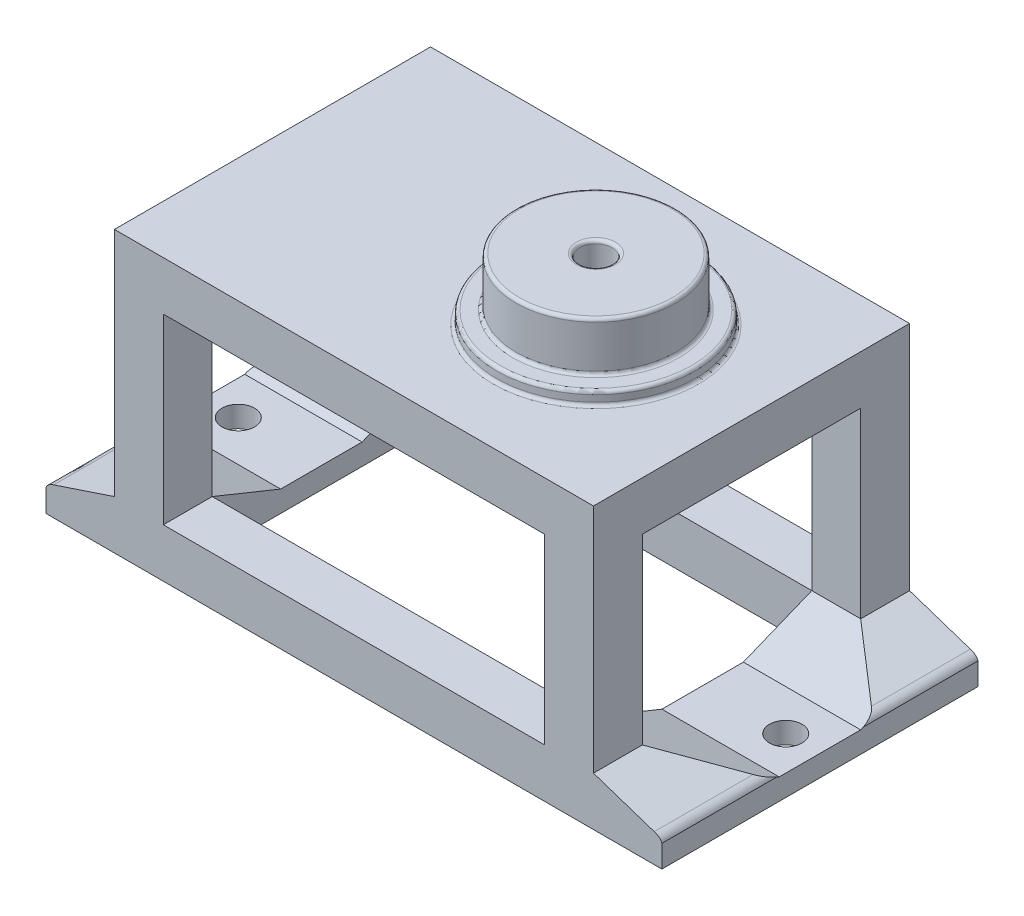
SolidWorks part; units mm, degrees
ref_plane "前视基准面" through (0, 0, 0) normal (0, 0, 1) x (1, 0, 0)
ref_plane "上视基准面" through (0, 0, 0) normal (0, 1, 0) x (1, 0, 0)
ref_plane "右视基准面" through (0, 0, 0) normal (1, 0, 0) x (0, 0, -1)
sketch "草图1" plane through (0, 0, 0) normal (0, 1, 0) x (1, 0, 0)
  line L1 (-11.7, 6.7) -> (11.7, 6.7)
  line L2 (-11.7, 6.7) -> (-11.7, -6.7)
  line L3 (-11.7, -6.7) -> (11.7, -6.7)
  line L4 (11.7, 6.7) -> (11.7, -6.7)
  line L5 (-11.7, 6.7) -> (11.7, -6.7) construction
  line L6 (-11.7, -6.7) -> (11.7, 6.7) construction
  line L7 (-14.7, 9.7) -> (14.7, 9.7)
  line L8 (-14.7, 9.7) -> (-14.7, -9.7)
  line L9 (-14.7, -9.7) -> (14.7, -9.7)
  line L10 (14.7, 9.7) -> (14.7, -9.7)
  line L11 (-14.7, 9.7) -> (14.7, -9.7) construction
  line L12 (-14.7, -9.7) -> (14.7, 9.7) construction
  point P0 (0, 0)
  point P6 (0, 0)
  dimension "D1" = 23.4
  dimension "D2" = 13.4
  dimension "D3" = 3
  dimension "D4" = 3
extrude "凸台-拉伸1" add sketch "草图1" along normal blind 16.4
sketch "草图2" plane through (0, 16.4, 0) normal (0, 1, 0) x (1, 0, 0)
  line L1 (-14.7, -9.7) -> (14.7, -9.7)
  line L2 (-14.7, -9.7) -> (-14.7, 9.7)
  line L3 (-14.7, 9.7) -> (14.7, 9.7)
  line L4 (14.7, -9.7) -> (14.7, 9.7)
  line L5 (-14.7, -9.7) -> (14.7, 9.7) construction
  line L6 (-14.7, 9.7) -> (14.7, -9.7) construction
  point P0 (0, 0)
extrude "凸台-拉伸2" add sketch "草图2" along normal blind 0.8
sketch "草图3" plane through (0, 17.2, 0) normal (0, 1, 0) x (1, 0, 0)
  line L0 (11.25, 0) -> (5.15, 0)
  line L1 (-11.25, 6.1) -> (11.25, 6.1)
  line L2 (-11.25, 6.1) -> (-11.25, -6.1)
  line L3 (-11.25, -6.1) -> (11.25, -6.1)
  line L4 (11.25, 6.1) -> (11.25, -6.1)
  line L5 (-11.25, 6.1) -> (11.25, -6.1) construction
  line L6 (-11.25, -6.1) -> (11.25, 6.1) construction
  circle A0 centre (5.15, 0) radius 6.1
  point P0 (0, 0)
  dimension "D1" = 22.5
  dimension "D2" = 12.2
extrude "凸台-拉伸3" add sketch "草图3" along normal blind 0.8
sketch "草图5" plane through (0, 18, 0) normal (0, 1, 0) x (1, 0, 0)
  circle A0 centre (5.15, 0) radius 4.9
  circle A1 centre (5.15, 0) radius 1
extrude "凸台-拉伸4" add sketch "草图5" along normal blind 3
fillet "圆角1" radius 0.2 6 edges at (5.15, 18, 6.1) (5.15, 21, 4.9) (5.15, 18, 4.9) (5.15, 17.2, 6.1) (5.15, 18, 1) (5.15, 21, 1)
sketch "草图6" plane through (0, 21, 0) normal (0, 1, 0) x (1, 0, 0)
sketch "草图7" plane through (-14.7, 0, 0) normal (-1, 0, 0) x (0, 0, 1)
  line L0 (9.7, 8.6) -> (-9.7, 8.6)
  line L1 (9.7, 17.2) -> (9.7, 0) construction
  line L2 (-9.7, 17.2) -> (-9.7, 0) construction
  line L3 (-9.7, 0) -> (9.7, 0) construction
  line L4 (6.7, 14.2) -> (-6.7, 14.2)
  line L5 (6.7, 14.2) -> (6.7, 3)
  line L6 (6.7, 3) -> (-6.7, 3)
  line L7 (-6.7, 14.2) -> (-6.7, 3)
  line L8 (6.7, 14.2) -> (-6.7, 3) construction
  line L9 (6.7, 3) -> (-6.7, 14.2) construction
  point P6 (0, 8.6)
  dimension "D1" = 3
  dimension "D2" = 3
extrude "切除-拉伸2" cut sketch "草图7" against normal blind 30 contours L4 L7 L0 L5 | L0 L7 L6 L5
sketch "草图8" plane through (0, 0, -9.7) normal (0, 0, -1) x (-1, 0, 0)
  line L0 (-14.7, 8.6) -> (14.7, 8.6)
  line L1 (-14.7, 17.2) -> (-14.7, 0) construction
  line L2 (14.7, 17.2) -> (14.7, 0) construction
  line L3 (-14.7, 17.2) -> (14.7, 17.2) construction
  line L4 (-11.7, 14.2) -> (11.7, 14.2)
  line L5 (-11.7, 14.2) -> (-11.7, 3)
  line L6 (-11.7, 3) -> (11.7, 3)
  line L7 (11.7, 14.2) -> (11.7, 3)
  line L8 (-11.7, 14.2) -> (11.7, 3) construction
  line L9 (-11.7, 3) -> (11.7, 14.2) construction
  point P6 (0, 8.6)
  dimension "D1" = 3
  dimension "D2" = 3
extrude "切除-拉伸3" cut sketch "草图8" against normal blind 30 contours L7 L4 L5 L0 | L7 L0 L5 L6
sketch "草图9" plane through (14.7, 0, 0) normal (1, 0, 0) x (0, 0, -1)
  line L1 (9.7, 0) -> (-9.7, 0)
  line L2 (9.7, 0) -> (9.7, 3)
  line L3 (9.7, 3) -> (-9.7, 3)
  line L4 (-9.7, 0) -> (-9.7, 3)
extrude "凸台-拉伸5" add sketch "草图9" along normal blind 4.2
sketch "草图10" plane through (0, 0, 9.7) normal (0, 0, 1) x (1, 0, 0)
  line L0 (18.9, 1.3692) -> (18.9, 1.6)
  line L1 (18.9, 3) -> (18.9, 0) construction
  line L2 (18.9, 3) -> (18.9, 1.6)
  line L3 (18.4866, 1.7378) -> (14.7, 3)
  line L4 (14.7, 3) -> (18.9, 3)
  spline S0 degree 2 poles (18.4297, 1.7568) (18.8199, 1.6361) (18.9, 1.3692) knots 0 0 0 0.659175 0.659175 0.659175
  line M6 (18.9, 0) -> (18.9, 3)
  line M7 (18.9, 3) -> (14.7, 3)
extrude "切除-拉伸4" cut sketch "草图10" against normal blind 20.2 contours L3 S0 M6 M7
sketch "草图11" plane through (14.7, 0, 0) normal (1, 0, 0) x (0, 0, -1)
  line L0 (6.7, 3) -> (-6.7, 3)
  line L1 (-9.7, 0) -> (9.7, 0) construction
  line L2 (6.7, 3) -> (-6.7, 3)
  line L3 (6.7, 3) -> (6.7, 1.3)
  line L4 (6.7, 1.3) -> (-6.7, 1.3)
  line L5 (-6.7, 3) -> (-6.7, 1.3)
  line L6 (2.5, 1.3) -> (-2.5, 1.3)
  line L7 (-2.5, 1.3) -> (-6.7, 3)
  line L8 (2.5, 1.3) -> (6.7, 3)
  point P11 (0, 1.3)
  dimension "D1" = 1.3
  dimension "D2" = 5
extrude "切除-拉伸5" cut sketch "草图11" along normal mid plane 10.2 contours L4 L8 L0 L7
sketch "草图12" plane through (0, 1.3, 0) normal (0, 1, 0) x (1, 0, 0)
  line L0 (18.9, 2.5) -> (11.7, 2.5) construction
  line L1 (18.9, -2.5) -> (14.7, -2.5)
  line L2 (18.9, -2.5) -> (18.9, 2.5)
  line L3 (18.9, 2.5) -> (14.7, 2.5)
  line L4 (14.7, -2.5) -> (14.7, 2.5)
  line L5 (14.7, -9.7) -> (14.7, 9.7) construction
  circle A0 centre (16.8, 0) radius 1
  dimension "D1" = 2
extrude "切除-拉伸6" cut sketch "草图12" against normal blind 2.2 contours A0
mirror "镜向1" about plane through (0, 0, 0) normal (1, 0, 0) of "切除-拉伸5", "切除-拉伸4", "切除-拉伸6", "凸台-拉伸5"
